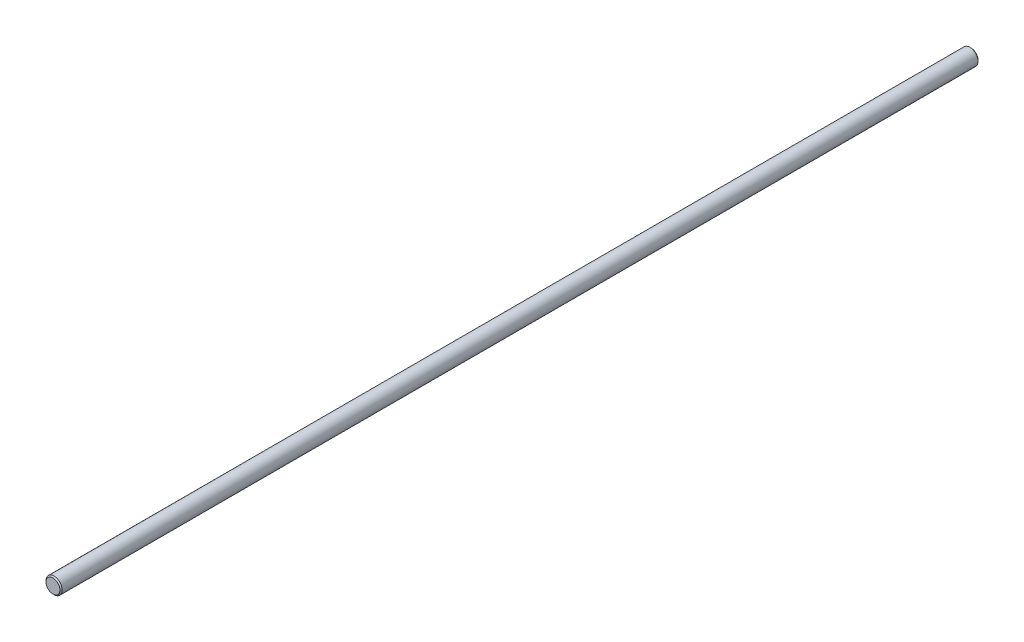
SolidWorks part; units mm, degrees
ref_plane "Front Plane" through (0, 0, 0) normal (0, 0, 1) x (1, 0, 0)
ref_plane "Top Plane" through (0, 0, 0) normal (0, 1, 0) x (1, 0, 0)
ref_plane "Right Plane" through (0, 0, 0) normal (1, 0, 0) x (0, 0, -1)
sketch "Sketch1" plane through (0, 0, 0) normal (0, 0, 1) x (1, 0, 0)
  line L0 (-3, 0) -> (3, 0) construction
  line L5 (0, 3) -> (0, -3) construction
  circle A1 centre (0, 0) radius 3
  point P7 (-3, 0)
  point P8 (3, 0)
  point P12 (0, -3)
  point P13 (0, 3)
  dimension "Diameter" = 6
sketch "Sketch2" plane through (0, 0, 0) normal (1, 0, 0) x (0, 0, -1)
  line L0 (-194, -3) -> (-194, 3) construction
  line L1 (200, -3) -> (-200, -3)
  line L2 (200, -3) -> (200, 3)
  line L3 (200, 3) -> (-200, 3)
  line L4 (-200, -3) -> (-200, 3)
  line L5 (200, -3) -> (-200, 3) construction
  line L6 (200, 3) -> (-200, -3) construction
  line L7 (194, -3) -> (194, 3) construction
  line L8 (-200, 2.58) -> (-199.58, 3) construction
  point P0 (0, 0)
  point P8 (-200, 3)
  point P9 (200, 3)
  point P14 (-194, 3)
  point P15 (-194, -3)
  point P16 (194, 3)
  point P17 (194, -3)
  point P25 (0, -3)
  dimension "Length" = 400
  dimension "D1" = 6
  dimension "D2" = 6
  dimension "Chamfer Typ," = 45
  dimension "D4" = 0.42
sketch "Sketch3" plane through (0, 0, 0) normal (0, 0, 1) x (1, 0, 0)
  circle A0 centre (0, 0) radius 3 construction
  circle A1 centre (0, 0) radius 3
extrude "Boss-Extrude1" add sketch "Sketch3" along normal blind 190 and the other way blind 150
chamfer "Chamfer1" distance 0.42 angle 45 2 edges at (3, 0, -150) (3, 0, 190)
equation "\"D1@Sketch2\"=\"Diameter@Sketch1\""
equation "\"D2@Sketch2\"=\"Diameter@Sketch1\""
equation "\"D1@Chamfer1\"=\"Diameter@Sketch1\"*.07"
equation "\"D4@Sketch2\"=\"Diameter@Sketch1\"*.07"
equation "\"D2@Chamfer1\"=\"Chamfer Typ,@Sketch2\""
